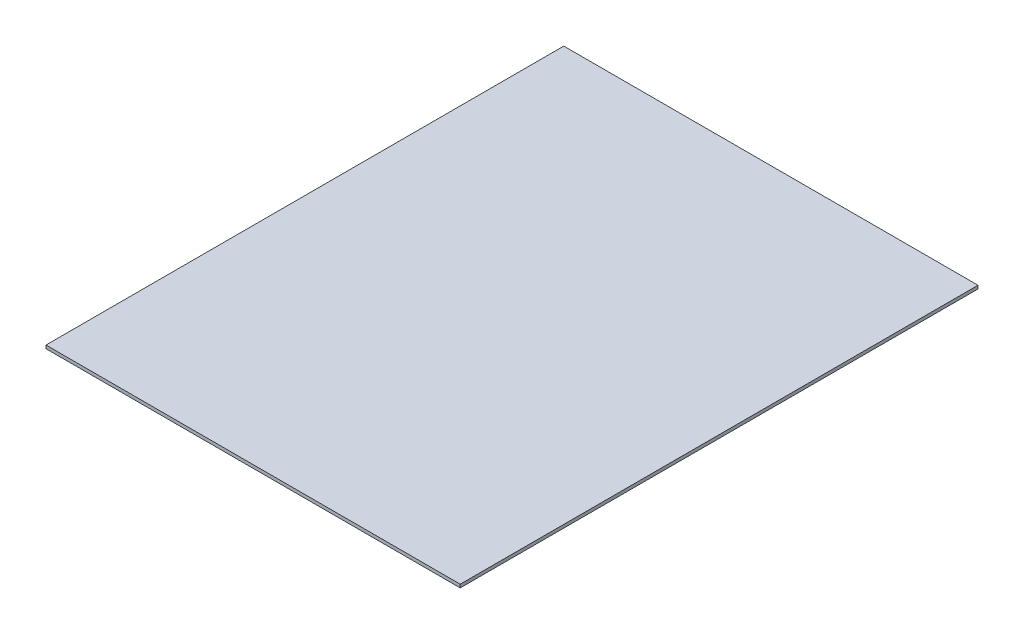
SolidWorks part; units mm, degrees
material "ABS PC"
ref_plane "Front Plane" through (0, 0, 0) normal (0, 0, 1) x (1, 0, 0)
ref_plane "Top Plane" through (0, 0, 0) normal (0, 1, 0) x (1, 0, 0)
ref_plane "Right Plane" through (0, 0, 0) normal (1, 0, 0) x (0, 0, -1)
sketch "Sketch1" plane through (0, 0, 0) normal (0, 1, 0) x (1, 0, 0)
  line L1 (0, 0) -> (406.4, 0)
  line L2 (0, 0) -> (0, 508)
  line L3 (0, 508) -> (406.4, 508)
  line L4 (406.4, 0) -> (406.4, 508)
  dimension "D1" = 406.4
  dimension "D2" = 508
extrude "Boss-Extrude1" add sketch "Sketch1" along normal blind 3.175
